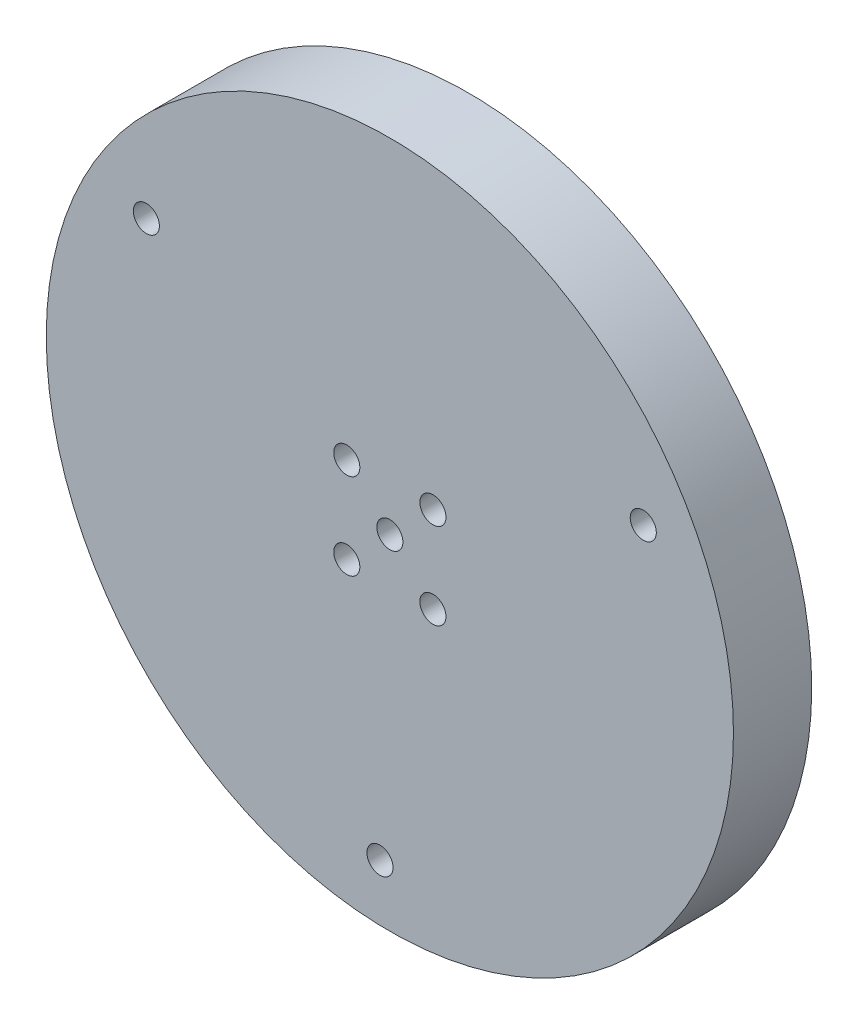
SolidWorks part; units mm, degrees
ref_plane "前视基准面" through (0, 0, 0) normal (0, 0, 1) x (1, 0, 0)
ref_plane "上视基准面" through (0, 0, 0) normal (0, 1, 0) x (1, 0, 0)
ref_plane "右视基准面" through (0, 0, 0) normal (1, 0, 0) x (0, 0, -1)
sketch "草图1" plane through (0, 0, 0) normal (0, 0, 1) x (1, 0, 0)
  circle A0 centre (0, 0) radius 39.5
extrude "凸台-拉伸1" add sketch "草图1" along normal blind 9
sketch "草图2" plane through (0, 0, 0) normal (0, 0, -1) x (-1, 0, 0)
  circle A0 centre (0, 0) radius 20
extrude "切除-拉伸1" cut sketch "草图2" against normal blind 5
sketch "草图3" plane through (0, 0, 0) normal (0, 0, -1) x (-1, 0, 0)
  circle A0 centre (1.1367, -32.9804) radius 1.5
  circle A1 centre (-29.1302, 15.5058) radius 1.5
  circle A2 centre (27.9935, 17.4746) radius 1.5
  point P8 (0, 0)
  dimension "D1" = 3
extrude "切除-拉伸2" cut sketch "草图3" against normal through all
sketch "草图4" plane through (0, 0, 5) normal (0, 0, -1) x (-1, 0, 0)
  circle A0 centre (0, 0) radius 1.5
  circle A1 centre (-4.9497, 4.9497) radius 1.5
  circle A2 centre (4.9497, 4.9497) radius 1.5
  circle A3 centre (4.9497, -4.9497) radius 1.5
  circle A4 centre (-4.9497, -4.9497) radius 1.5
extrude "切除-拉伸3" cut sketch "草图4" against normal through all
